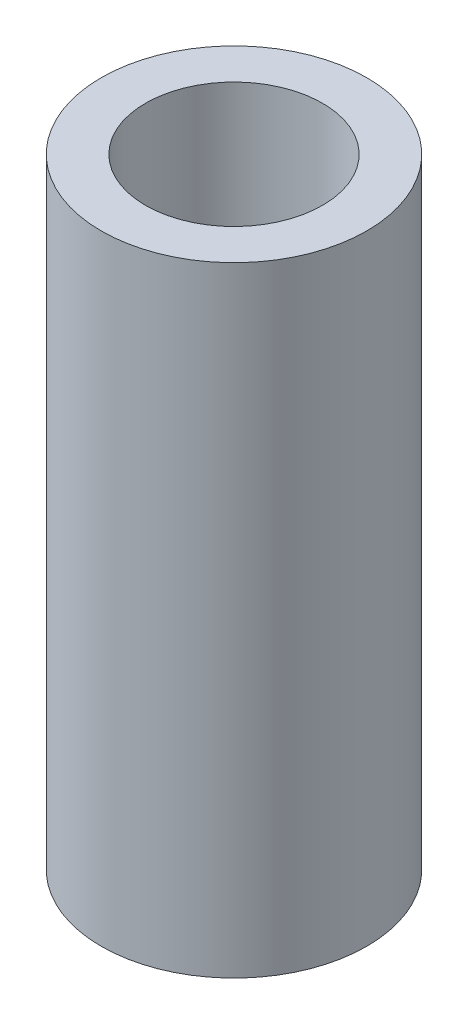
SolidWorks part; units mm, degrees
material "Brass"
ref_plane "Front Plane" through (0, 0, 0) normal (0, 0, 1) x (1, 0, 0)
ref_plane "Top Plane" through (0, 0, 0) normal (0, 1, 0) x (1, 0, 0)
ref_plane "Right Plane" through (0, 0, 0) normal (1, 0, 0) x (0, 0, -1)
sketch "Sketch1" plane through (0, 0, 0) normal (0, 0, 1) x (1, 0, 0)
  line L0 (-3, 0) -> (0, 0)
  line L1 (0, 0) -> (0, 14)
  line L3 (0, 14) -> (-3, 14)
  line L5 (-3, 14) -> (-3, 0)
  line L6 (0, -2.69) -> (0, 16.8158) construction
  dimension "D1" = 14
  dimension "D2" = 3
revolve "Revolve1" add sketch "Sketch1" angle 360 about L6
sketch "Sketch2" plane through (0, 0, 0) normal (0, 1, 0) x (1, 0, 0)
  circle A0 centre (0, 0) radius 2
  dimension "D1" = 4
extrude "Cut-Extrude1" cut sketch "Sketch2" along normal through all
